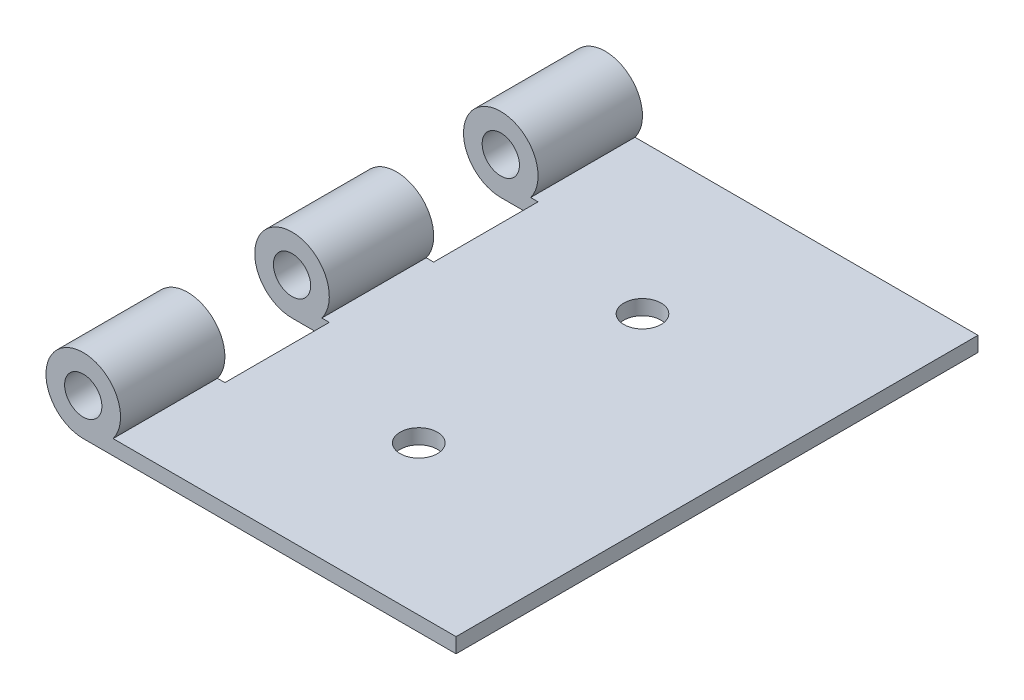
SolidWorks part; units mm, degrees
ref_plane "Front Plane" through (0, 0, 0) normal (0, 0, 1) x (1, 0, 0)
ref_plane "Top Plane" through (0, 0, 0) normal (0, 1, 0) x (1, 0, 0)
ref_plane "Right Plane" through (0, 0, 0) normal (1, 0, 0) x (0, 0, -1)
sketch "Sketch1" plane through (0, 0, 0) normal (0, 1, 0) x (1, 0, 0)
  line L1 (-25, 35) -> (25, 35)
  line L2 (-25, 35) -> (-25, -35)
  line L3 (-25, -35) -> (25, -35)
  line L4 (25, 35) -> (25, -35)
  line L5 (-25, 35) -> (25, -35) construction
  line L6 (-25, -35) -> (25, 35) construction
  point P0 (0, 0)
  dimension "D1" = 70
  dimension "D2" = 50
extrude "Boss-Extrude1" add sketch "Sketch1" along normal blind 2
sketch "Sketch2" plane through (0, 0, 35) normal (0, 0, 1) x (1, 0, 0)
  circle A0 centre (-25, 5) radius 2.5
  circle A1 centre (-25, 5) radius 5
  dimension "D1" = 10
  dimension "D2" = 5
extrude "Boss-Extrude2" add sketch "Sketch2" against normal up to surface (70 mm away) up to face at (0, 1, -35)
sketch "Sketch3" plane through (0, 2, 0) normal (0, 1, 0) x (1, 0, 0)
  line L0 (25, -35) -> (25, 35) construction
  line L1 (-21, -35) -> (25, -35) construction
  line L2 (25, 35) -> (-21, 35) construction
  circle A0 centre (0, 15) radius 2.5
  circle A1 centre (0, -15) radius 2.5
  dimension "D1" = 5
  dimension "D2" = 5
  dimension "D4" = 25
  dimension "D5" = 20
  dimension "D6" = 20
  dimension "D3" = 25
extrude "Cut-Extrude1" cut sketch "Sketch3" against normal through all
sketch "Sketch5" plane through (0, 2, 0) normal (0, 1, 0) x (1, 0, 0)
  line L0 (-30, 35) -> (-30, -35) construction
  line L1 (-30, -7) -> (-20, -7)
  line L2 (-30, -7) -> (-30, -21)
  line L3 (-30, -21) -> (-20, -21)
  line L4 (-20, -7) -> (-20, -21)
  line L5 (-20, -35) -> (-20, 35) construction
  line L6 (-30, -35) -> (-20, -35) construction
  line L7 (-30, 21) -> (-20, 21)
  line L8 (-30, 21) -> (-30, 7)
  line L9 (-30, 7) -> (-20, 7)
  line L10 (-20, 21) -> (-20, 7)
  dimension "D1" = 14
  dimension "D2" = 14
  dimension "D3" = 14
  dimension "D4" = 14
extrude "Cut-Extrude2" cut sketch "Sketch5" against normal through all both and the other way through all
